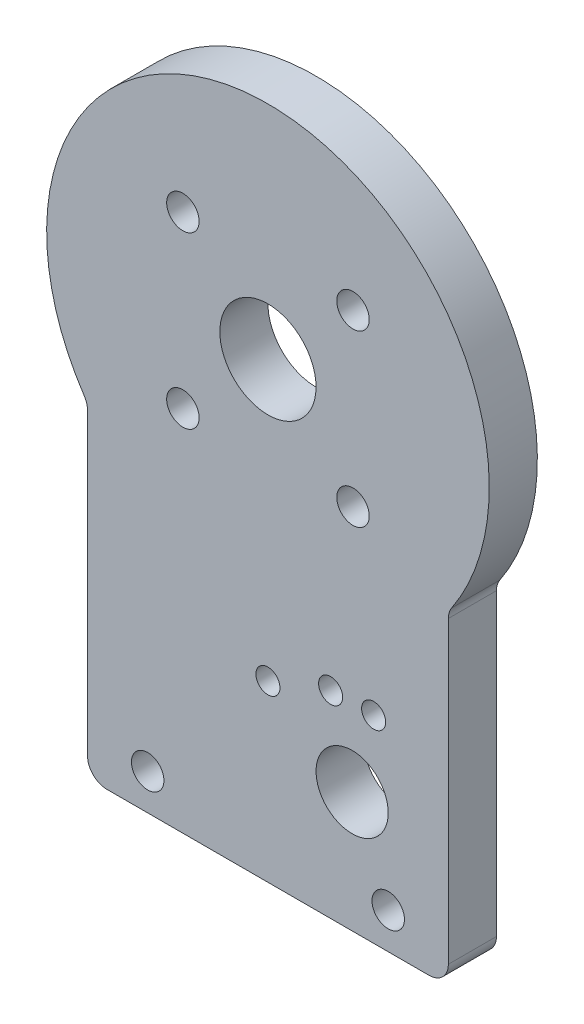
SolidWorks part; units mm, degrees
material "Aleación 1060"
ref_plane "Alzado" through (0, 0, 0) normal (0, 0, 1) x (1, 0, 0)
ref_plane "Planta" through (0, 0, 0) normal (0, 1, 0) x (1, 0, 0)
ref_plane "Vista lateral" through (0, 0, 0) normal (1, 0, 0) x (0, 0, -1)
sketch "Croquis1" plane through (0, 0, 0) normal (0, 0, 1) x (1, 0, 0)
  line L0 (0, 0) -> (-7.0711, -7.0711) construction
  line L1 (0, -18.4) -> (-15, -18.4) construction
  line L2 (-15, -10.6565) -> (-15, -37.6565)
  line L3 (0, -4) -> (0, -18.4) construction
  line L4 (15, -10.6565) -> (15, -37.6565)
  line L5 (-15, -37.6565) -> (15, -37.6565)
  arc A0 (15, -10.6565) -> (-15, -10.6565) centre (0, 0) ccw
  circle A1 centre (-7.0711, -7.0711) radius 1.35
  circle A2 centre (-7.0711, 7.0711) radius 1.35
  circle A3 centre (7.0711, 7.0711) radius 1.35
  circle A4 centre (7.0711, -7.0711) radius 1.35
  circle A5 centre (0, 0) radius 4
  circle A6 centre (-10, -34.6565) radius 1.35
  circle A7 centre (10, -34.6565) radius 1.35
  point P14 (0, 0)
  dimension "D1" = 36.8
  dimension "D3" = 2.7
  dimension "D5" = 8
  dimension "D8" = 5
  dimension "D10" = 2.7
  dimension "D2" = 10
  dimension "D6" = 15
  dimension "D7" = 27
  dimension "D9" = 3
  dimension "D4" = 4
extrude "Saliente-Extruir1" add sketch "Croquis1" along normal blind 4
sketch "Croquis2" plane through (0, 0, 4) normal (0, 0, 1) x (1, 0, 0)
  line L0 (-15, -37.6565) -> (15, -37.6565) construction
  line L2 (15, -37.6565) -> (15, -10.6565) construction
  line L3 (7, -27.6565) -> (7, -17.6565) construction
  circle A0 centre (7, -27.6565) radius 3
  circle A1 centre (5.2111, -21.2342) radius 1
  circle A2 centre (8.7889, -21.2342) radius 1
  dimension "D1" = 10
  dimension "D4" = 2
  dimension "D6" = 6
  dimension "D2" = 8
  dimension "D3" = 10
  dimension "D5" = 4
extrude "Cortar-Extruir1" cut sketch "Croquis2" against normal up to vertex (4 mm away)
fillet "Redondeo1" radius 1.6 4 edges at (15, -10.6565, 2) (15, -37.6565, 2) (-15, -10.6565, 2) (-15, -37.6565, 2)
sketch "Croquis3" plane through (0, 0, 4) normal (0, 0, 1) x (1, 0, 0)
  line L0 (-13.4, -37.6565) -> (13.4, -37.6565) construction
  circle A0 centre (0, -23.1565) radius 1
  dimension "D1" = 2
  dimension "D2" = 14.5
extrude "Cortar-Extruir2" cut sketch "Croquis3" against normal up to vertex (4 mm away)
